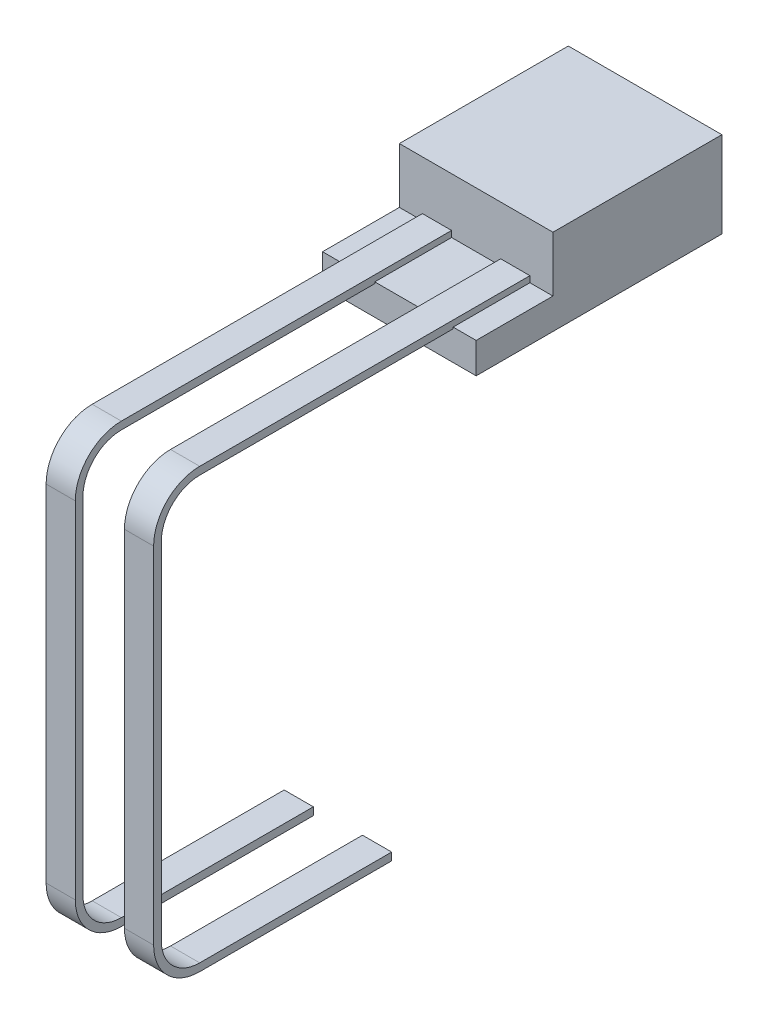
SolidWorks part; units mm, degrees
ref_plane "Front Plane" through (0, 0, 0) normal (0, 0, 1) x (1, 0, 0)
ref_plane "Top Plane" through (0, 0, 0) normal (0, 1, 0) x (1, 0, 0)
ref_plane "Right Plane" through (0, 0, 0) normal (1, 0, 0) x (0, 0, -1)
sketch "Sketch1" plane through (0, 0, 0) normal (0, 1, 0) x (1, 0, 0)
  line L1 (-1, 0) -> (1, 0)
  line L2 (-1, 0) -> (-1, -3.2)
  line L3 (-1, -3.2) -> (1, -3.2)
  line L4 (1, 0) -> (1, -3.2)
  dimension "D1" = 3.2
  dimension "D2" = 2
extrude "Boss-Extrude1" add sketch "Sketch1" along normal blind 1.12
sketch "Sketch2" plane through (0, 0, 0) normal (1, 0, 0) x (0, 0, -1)
  line L1 (-3.6338, 1.465) -> (-2.2, 1.465)
  line L2 (-3.6338, 1.465) -> (-3.6338, 0.4)
  line L3 (-3.6338, 0.4) -> (-2.2, 0.4)
  line L4 (-2.2, 1.465) -> (-2.2, 0.4)
  dimension "D1" = 0.4
  dimension "D2" = 2.2
extrude "Cut-Extrude1" cut sketch "Sketch2" against normal mid plane 10
sketch "Sketch3" plane through (0, 0, 2.2) normal (0, 0, 1) x (1, 0, 0)
  line L1 (0.32, 0.48) -> (0.7, 0.48)
  line L2 (0.32, 0.48) -> (0.32, 0.38)
  line L3 (0.32, 0.38) -> (0.7, 0.38)
  line L4 (0.7, 0.48) -> (0.7, 0.38)
  point P4 (0.51, 0.38)
  dimension "D1" = 0.38
  dimension "D2" = 0.38
  dimension "D3" = 0.7
  dimension "D4" = 0.1
sketch3d "3DSketch1"
  line L0 (0.51, 0.38, 2.2) -> (0.51, 0.38, 6.5)
  line L1 (0.51, -0.12, 7) -> (0.51, -4.62, 7)
  line L2 (0.51, -5.12, 6.5) -> (0.51, -5.12, 4)
  arc A0 (0.51, 0.38, 6.5) -> (0.51, -0.12, 7) centre (0.51, -0.12, 6.5) ccw
  arc A1 (0.51, -4.62, 7) -> (0.51, -5.12, 6.5) centre (0.51, -4.62, 6.5) ccw
  point P6 (0.51, 0.38, 7)
  point P7 (1.01, -0.12, 6.5)
  point P12 (1.01, -4.62, 6.5)
  dimension "D1" = 0.5
  dimension "D4" = 0.5
  dimension "D2" = 4.8
  dimension "D3" = 5.5
  dimension "D5" = 3
sweep "Sweep1" add profiles "Sketch3" path "3DSketch1"
mirror "Mirror1" about plane through (0, 0, 0) normal (1, 0, 0) of "Sweep1"
